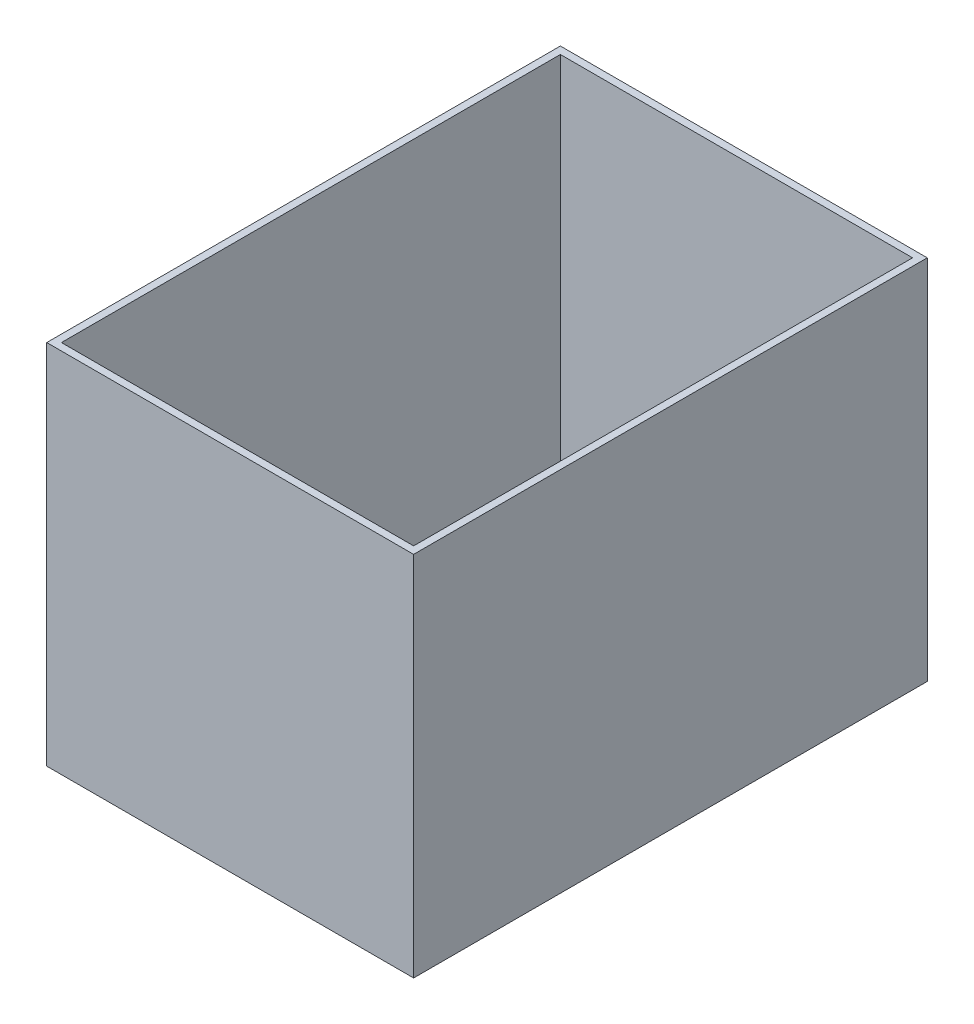
SolidWorks part; units mm, degrees
ref_plane "Front Plane" through (0, 0, 0) normal (0, 0, 1) x (1, 0, 0)
ref_plane "Top Plane" through (0, 0, 0) normal (0, 1, 0) x (1, 0, 0)
ref_plane "Right Plane" through (0, 0, 0) normal (1, 0, 0) x (0, 0, -1)
sketch "Sketch1" plane through (0, 0, 0) normal (0, 1, 0) x (1, 0, 0)
  line L1 (-250, 350) -> (250, 350)
  line L2 (-250, 350) -> (-250, -350)
  line L3 (-250, -350) -> (250, -350)
  line L4 (250, 350) -> (250, -350)
  line L5 (-250, 350) -> (250, -350) construction
  line L6 (-250, -350) -> (250, 350) construction
  point P0 (0, 0)
  dimension "D1" = 700
  dimension "D2" = 500
extrude "Boss-Extrude1" add sketch "Sketch1" along normal blind 500
shell "Shell1" thickness 10
